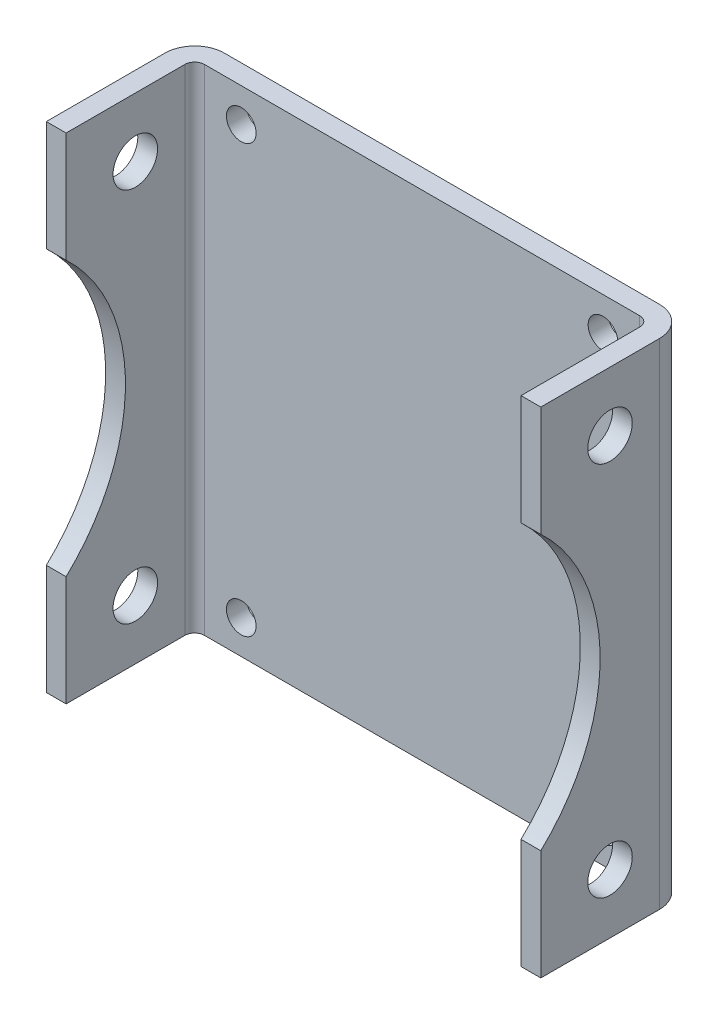
SolidWorks part; units mm, degrees
material "ABS"
ref_plane "Front Plane" through (0, 0, 0) normal (0, 0, 1) x (1, 0, 0)
ref_plane "Top Plane" through (0, 0, 0) normal (0, 1, 0) x (1, 0, 0)
ref_plane "Right Plane" through (0, 0, 0) normal (1, 0, 0) x (0, 0, -1)
sketch "Sketch1" plane through (0, 0, 0) normal (0, 1, 0) x (1, 0, 0)
  line L0 (-2, 0) -> (-2, 12)
  line L1 (1, 15) -> (45, 15)
  line L2 (48, 12) -> (48, 0)
  line L3 (48, 0) -> (46, 0)
  line L4 (46, 0) -> (46, 12)
  line L5 (45, 13) -> (1, 13)
  line L6 (0, 12) -> (0, 0)
  line L7 (0, 0) -> (-2, 0)
  arc A0 (45, 15) -> (48, 12) centre (45, 12) cw
  arc A1 (-2, 12) -> (1, 15) centre (1, 12) cw
  arc A2 (46, 12) -> (45, 13) centre (45, 12) ccw
  arc A3 (1, 13) -> (0, 12) centre (1, 12) ccw
  point P10 (48, 15)
  point P13 (-2, 15)
  dimension "D6" = 3
  dimension "D7" = 1
  dimension "D1" = 2
  dimension "D2" = 2
  dimension "D3" = 2
  dimension "D4" = 15
  dimension "D5" = 50
extrude "Boss-Extrude1" add sketch "Sketch1" along normal blind 50
sketch "Sketch2" plane through (48, 0, 0) normal (1, 0, 0) x (0, 0, -1)
  line L0 (0, 50) -> (12, 50) construction
  line L1 (15, 50) -> (15, 0) construction
  line L2 (7, 50) -> (7, 0) construction
  line L3 (0, 0) -> (12, 0) construction
  circle A0 centre (-13, 25) radius 19
  circle A1 centre (7, 44) radius 2.25
  circle A2 centre (7, 6) radius 2.25
  dimension "D1" = 25
  dimension "D3" = 38
  dimension "D5" = 4.5
  dimension "D6" = 4.5
  dimension "D2" = 28
  dimension "D4" = 8
  dimension "D7" = 6
  dimension "D8" = 6
extrude "Cut-Extrude1" cut sketch "Sketch2" against normal through all
sketch "Sketch3" plane through (0, 0, -15) normal (0, 0, -1) x (-1, 0, 0)
  line L0 (-45, 0) -> (-1, 0) construction
  line L1 (-48, 50) -> (-48, 0) construction
  circle A0 centre (-41.29, 46.59) radius 1.5
  circle A1 centre (-4.71, 46.59) radius 1.5
  circle A2 centre (-4.71, 3.41) radius 1.5
  circle A3 centre (-41.29, 3.41) radius 1.5
  dimension "D3" = 3
  dimension "D4" = 3
  dimension "D5" = 3
  dimension "D6" = 3
  dimension "D1" = 43.18
  dimension "D2" = 36.58
  dimension "D7" = 3.41
  dimension "D8" = 6.71
extrude "Cut-Extrude2" cut sketch "Sketch3" against normal blind 10
